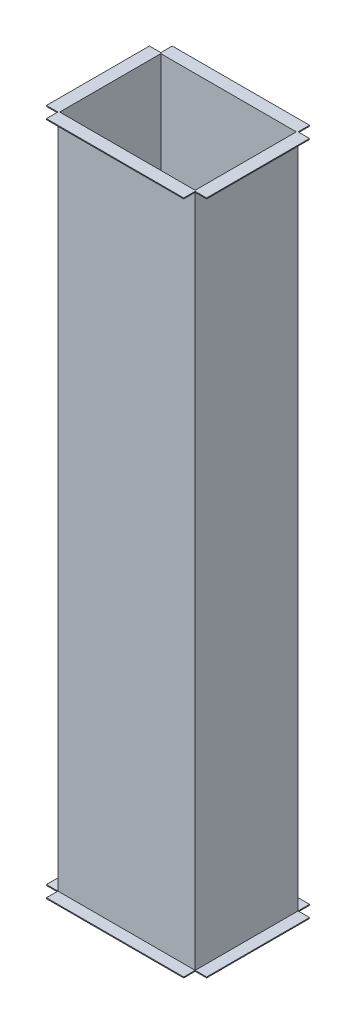
SolidWorks part; units mm, degrees
ref_plane "Alzado" through (0, 0, 0) normal (0, 0, 1) x (1, 0, 0)
ref_plane "Planta" through (0, 0, 0) normal (0, 1, 0) x (1, 0, 0)
ref_plane "Vista lateral" through (0, 0, 0) normal (1, 0, 0) x (0, 0, -1)
sketch "Croquis1" plane through (0, 0, 0) normal (0, 1, 0) x (1, 0, 0)
  line L1 (152.4, 114.3) -> (-152.4, 114.3)
  line L2 (152.4, 114.3) -> (152.4, -114.3)
  line L3 (152.4, -114.3) -> (-152.4, -114.3)
  line L4 (-152.4, 114.3) -> (-152.4, -114.3)
  line L5 (152.4, 114.3) -> (-152.4, -114.3) construction
  line L6 (152.4, -114.3) -> (-152.4, 114.3) construction
  point P0 (0, 0)
  dimension "D1" = 228.6
  dimension "D2" = 304.8
extrude "Saliente-Extruir1" add sketch "Croquis1" along normal blind 1500
shell "Vaciado1" thickness 2
sketch "Croquis2" plane through (0, 1500, 0) normal (0, 1, 0) x (1, 0, 0)
  line L1 (-152.4, 114.3) -> (-177.8, 114.3)
  line L2 (-152.4, 114.3) -> (-152.4, -114.3)
  line L3 (-152.4, -114.3) -> (-177.8, -114.3)
  line L8 (-177.8, 114.3) -> (-177.8, -114.3)
  line L9 (-152.4, -114.3) -> (152.4, -114.3)
  line L10 (-152.4, -114.3) -> (-152.4, -139.7)
  line L11 (-152.4, -139.7) -> (152.4, -139.7)
  line L28 (152.4, -114.3) -> (152.4, -139.7)
  line L29 (152.4, 114.3) -> (177.8, 114.3)
  line L30 (152.4, 114.3) -> (152.4, -114.3)
  line L31 (152.4, -114.3) -> (177.8, -114.3)
  line L32 (177.8, 114.3) -> (177.8, -114.3)
  line L33 (-152.4, 114.3) -> (152.4, 114.3)
  line L34 (-152.4, 114.3) -> (-152.4, 139.7)
  line L35 (-152.4, 139.7) -> (152.4, 139.7)
  line L36 (152.4, 114.3) -> (152.4, 139.7)
  dimension "D1" = 25.4
  dimension "D2" = 25.4
  dimension "D3" = 25.4
  dimension "D4" = 25.4
extrude "Saliente-Extruir2" add sketch "Croquis2" against normal blind 2
ref_plane "Plano1" through (0, 750, 0) normal (0, 1, 0) x (1, 0, 0)
mirror "Simetría1" about plane through (0, 750, 0) normal (0, 1, 0) of "Saliente-Extruir2"
